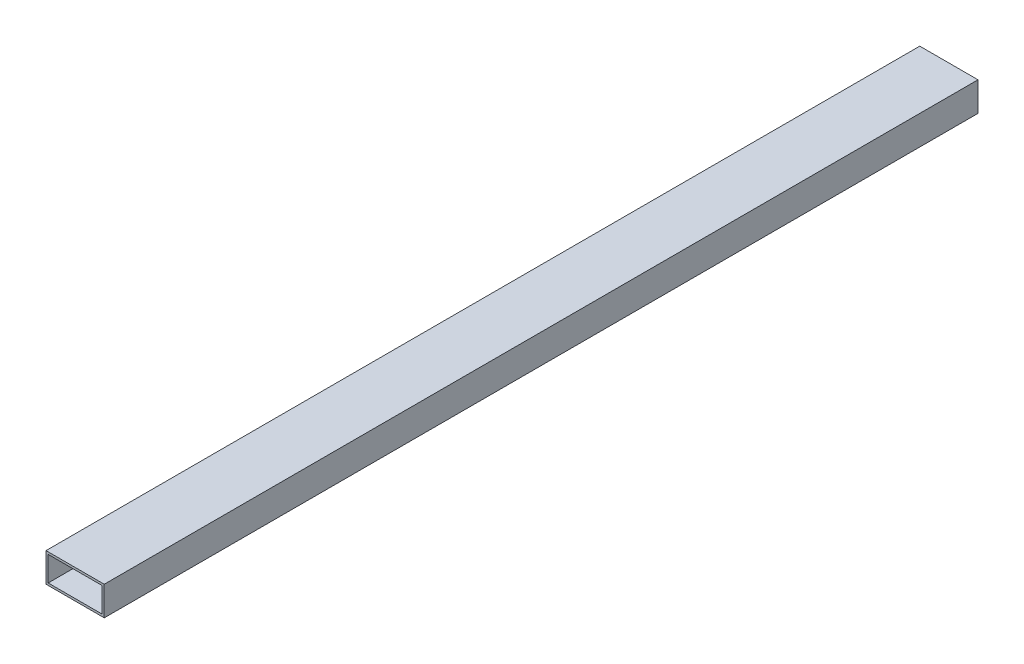
SolidWorks part; units mm, degrees
ref_plane "Спереди" through (0, 0, 0) normal (0, 0, 1) x (1, 0, 0)
ref_plane "Сверху" through (0, 0, 0) normal (0, 1, 0) x (1, 0, 0)
ref_plane "Справа" through (0, 0, 0) normal (1, 0, 0) x (0, 0, -1)
sketch "Эскиз1" plane through (0, 0, 0) normal (0, 0, 1) x (1, 0, 0)
  line L0 (-20, 0) -> (20, 0)
  line L1 (20, 0) -> (20, 20)
  line L2 (20, 20) -> (-20, 20)
  line L3 (-20, 20) -> (-20, 0)
  line L4 (-18.5, 18.5) -> (18.5, 18.5)
  line L5 (18.5, 18.5) -> (18.5, 1.5)
  line L6 (18.5, 1.5) -> (-18.5, 1.5)
  line L7 (-18.5, 1.5) -> (-18.5, 18.5)
  dimension "D1" = 40
  dimension "D2" = 20
  dimension "D3" = 1.5
  dimension "D4" = 1.5
  dimension "D5" = 37
  dimension "D6" = 17
extrude "Бобышка-Вытянуть1" add sketch "Эскиз1" along normal blind 600
